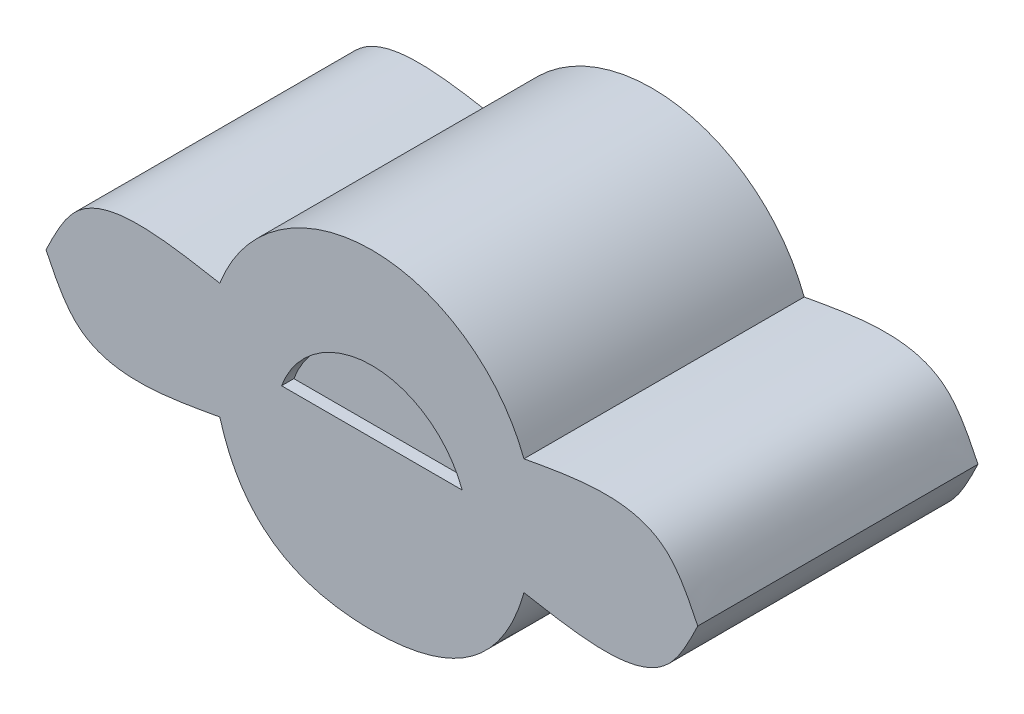
SolidWorks part; units mm, degrees
ref_plane "Front Plane" through (0, 0, 0) normal (0, 0, 1) x (1, 0, 0)
ref_plane "Top Plane" through (0, 0, 0) normal (0, 1, 0) x (1, 0, 0)
ref_plane "Right Plane" through (0, 0, 0) normal (1, 0, 0) x (0, 0, -1)
sketch "Sketch1" plane through (0, 0, 0) normal (0, 0, 1) x (1, 0, 0)
  line L0 (0, 2.0654) -> (0, -3.7766) construction
  line L1 (0, 0.0334) -> (-5.334, 0.0334) construction
  line L2 (0, 2.0654) -> (-11.43, 2.0654) construction
  line L3 (-11.43, 3.7766) -> (-11.43, 1.834) construction
  line L4 (0, -3.7766) -> (-4.5881, -3.7766) construction
  line L5 (-11.43, 2.0654) -> (11.43, 2.0654) construction
  line L6 (-3.1679, 2.0654) -> (3.1679, 2.0654)
  arc A2 (-3.1679, 2.0654) -> (3.1679, 2.0654) centre (0, 0.8887) cw
  arc A3 (-5.334, 4.0974) -> (5.334, 4.0974) centre (0, 2.0654) cw
  spline S0 degree 3 poles (-5.334, 0.0334) (-4.5995, -2.5799) (-2.822, -3.7766) (0, -3.7766) knots 0 0 0 0 1 1 1 1
  spline S1 degree 3 poles (-11.43, 2.0654) (-11.1219, 1.4299) (-10.0318, -0.8188) (-7.2963, -0.3226) (-5.334, 0.0334) knots 0 0 0 0 0.282634 1 1 1 1
  spline S2 degree 3 poles (5.334, 0.0334) (4.5995, -2.5799) (2.822, -3.7766) (0, -3.7766) knots 0 0 0 0 1 1 1 1
  spline S3 degree 3 poles (11.43, 2.0654) (11.1219, 1.4299) (10.0318, -0.8188) (7.2963, -0.3226) (5.334, 0.0334) knots 0 0 0 0 0.282634 1 1 1 1
  spline S4 degree 3 poles (11.43, 2.0654) (11.1219, 2.701) (10.0318, 4.9496) (7.2963, 4.4534) (5.334, 4.0974) knots 0 0 0 0 0.282634 1 1 1 1
  spline S5 degree 3 poles (-11.43, 2.0654) (-11.1219, 2.701) (-10.0318, 4.9496) (-7.2963, 4.4534) (-5.334, 4.0974) knots 0 0 0 0 0.282634 1 1 1 1
  dimension "D5" = 5.7079
  dimension "D8" = 3.3794
  dimension "D1" = 5.842
  dimension "D2" = 5.334
  dimension "D3" = 9.1762
  dimension "D4" = 22.86
  dimension "D6" = 6.3359
sketch "Sketch2" plane through (0, 0, 0) normal (0, 0, 1) x (1, 0, 0)
  line L0 (0, 2.0654) -> (0, -3.7766) construction
  line L1 (0, 0.0334) -> (-5.334, 0.0334) construction
  line L2 (0, 2.0654) -> (-11.43, 2.0654) construction
  line L3 (-11.43, 3.7766) -> (-11.43, 1.834) construction
  line L4 (0, -3.7766) -> (-4.5881, -3.7766) construction
  line L5 (-11.43, 2.0654) -> (11.43, 2.0654) construction
  line L6 (-3.1679, 2.0654) -> (3.1679, 2.0654)
  arc A2 (-3.1679, 2.0654) -> (3.1679, 2.0654) centre (0, 0.8887) cw
  arc A3 (-5.334, 4.0974) -> (5.334, 4.0974) centre (0, 2.0654) cw
  spline S0 degree 3 poles (-5.334, 0.0334) (-4.5995, -2.5799) (-2.822, -3.7766) (0, -3.7766) knots 0 0 0 0 1 1 1 1
  spline S1 degree 3 poles (-11.43, 2.0654) (-11.1219, 1.4299) (-10.0318, -0.8188) (-7.2963, -0.3226) (-5.334, 0.0334) knots 0 0 0 0 0.282634 1 1 1 1
  spline S2 degree 3 poles (5.334, 0.0334) (4.5995, -2.5799) (2.822, -3.7766) (0, -3.7766) knots 0 0 0 0 1 1 1 1
  spline S3 degree 3 poles (11.43, 2.0654) (11.1219, 1.4299) (10.0318, -0.8188) (7.2963, -0.3226) (5.334, 0.0334) knots 0 0 0 0 0.282634 1 1 1 1
  spline S4 degree 3 poles (11.43, 2.0654) (11.1219, 2.701) (10.0318, 4.9496) (7.2963, 4.4534) (5.334, 4.0974) knots 0 0 0 0 0.282634 1 1 1 1
  spline S5 degree 3 poles (-11.43, 2.0654) (-11.1219, 2.701) (-10.0318, 4.9496) (-7.2963, 4.4534) (-5.334, 4.0974) knots 0 0 0 0 0.282634 1 1 1 1
  dimension "D8" = 3.3794
  dimension "D1" = 5.842
  dimension "D2" = 5.334
  dimension "D3" = 9.1762
  dimension "D4" = 22.86
sketch "Sketch3" plane through (0, 0, 0) normal (0, 0, 1) x (1, 0, 0)
  line L0 (0, 2.0654) -> (0, -3.7766) construction
  line L1 (0, 0.0334) -> (-5.334, 0.0334) construction
  line L2 (0, 2.0654) -> (-11.43, 2.0654) construction
  line L3 (-11.43, 3.7766) -> (-11.43, 1.834) construction
  line L4 (0, -3.7766) -> (-4.5881, -3.7766) construction
  line L5 (-11.43, 2.0654) -> (11.43, 2.0654) construction
  arc A3 (-5.334, 4.0974) -> (5.334, 4.0974) centre (0, 2.0654) cw
  spline S0 degree 3 poles (-5.334, 0.0334) (-4.5995, -2.5799) (-2.822, -3.7766) (0, -3.7766) knots 0 0 0 0 1 1 1 1
  spline S1 degree 3 poles (-11.43, 2.0654) (-11.1219, 1.4299) (-10.0318, -0.8188) (-7.2963, -0.3226) (-5.334, 0.0334) knots 0 0 0 0 0.282634 1 1 1 1
  spline S2 degree 3 poles (5.334, 0.0334) (4.5995, -2.5799) (2.822, -3.7766) (0, -3.7766) knots 0 0 0 0 1 1 1 1
  spline S3 degree 3 poles (11.43, 2.0654) (11.1219, 1.4299) (10.0318, -0.8188) (7.2963, -0.3226) (5.334, 0.0334) knots 0 0 0 0 0.282634 1 1 1 1
  spline S4 degree 3 poles (11.43, 2.0654) (11.1219, 2.701) (10.0318, 4.9496) (7.2963, 4.4534) (5.334, 4.0974) knots 0 0 0 0 0.282634 1 1 1 1
  spline S5 degree 3 poles (-11.43, 2.0654) (-11.1219, 2.701) (-10.0318, 4.9496) (-7.2963, 4.4534) (-5.334, 4.0974) knots 0 0 0 0 0.282634 1 1 1 1
  dimension "D1" = 5.842
  dimension "D2" = 5.334
  dimension "D4" = 22.86
extrude "Boss-Extrude1" add sketch "Sketch1" along normal blind 9.8298
extrude "Boss-Extrude2" add sketch "Sketch2" along normal blind 9.398 contours A2 L6
